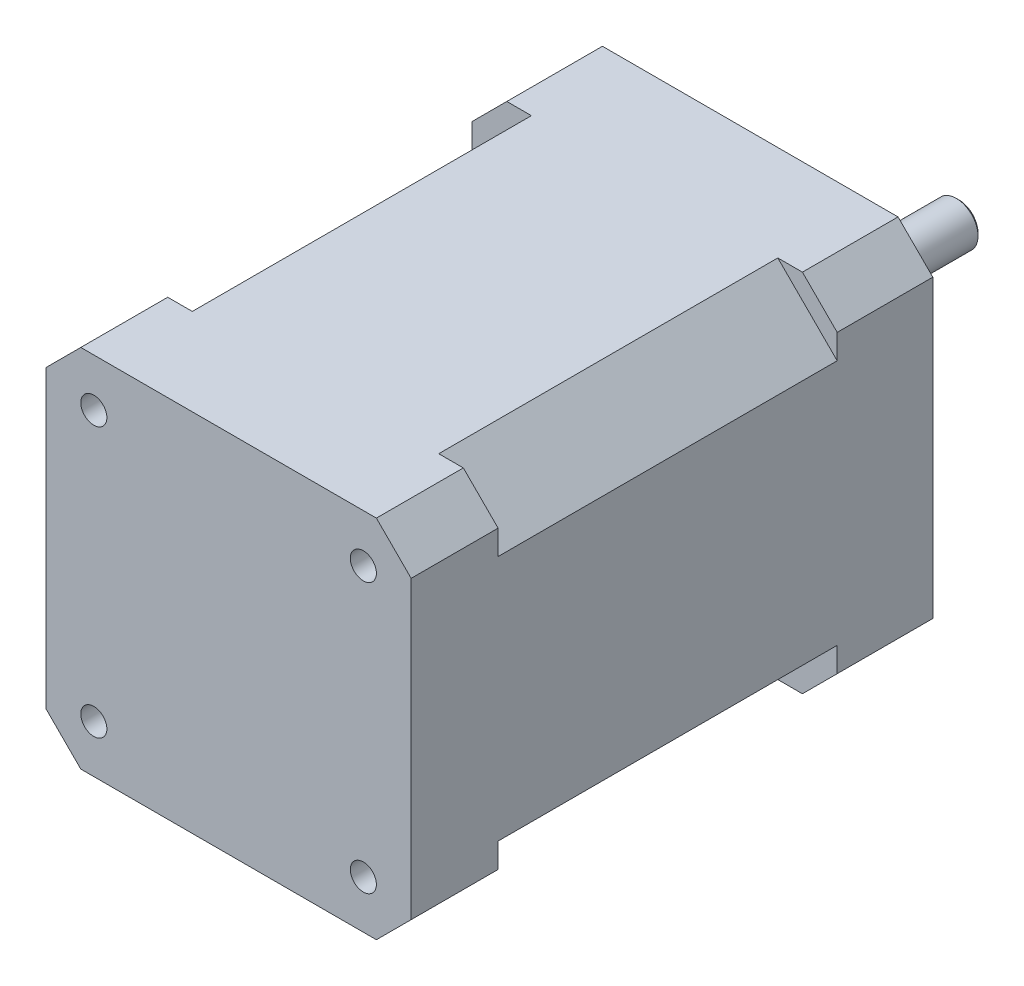
SolidWorks part; units mm, degrees
material "Простая углеродистая сталь"
ref_plane "Спереди" through (0, 0, 0) normal (0, 0, 1) x (1, 0, 0)
ref_plane "Сверху" through (0, 0, 0) normal (0, 1, 0) x (1, 0, 0)
ref_plane "Справа" through (0, 0, 0) normal (1, 0, 0) x (0, 0, -1)
sketch "Эскиз1" plane through (0, 0, 0) normal (0, 0, 1) x (1, 0, 0)
  line L1 (-33.4925, 25.7024) -> (8.5075, 25.7024)
  line L2 (-33.4925, 25.7024) -> (-33.4925, -16.2976)
  line L3 (-33.4925, -16.2976) -> (8.5075, -16.2976)
  line L4 (8.5075, 25.7024) -> (8.5075, -16.2976)
  dimension "D1" = 42
  dimension "D2" = 42
extrude "Бобышка-Вытянуть1" add sketch "Эскиз1" along normal blind 60
sketch "Эскиз2" plane through (0, 0, 0) normal (0, 0, -1) x (-1, 0, 0)
  line L0 (12.4925, 25.7024) -> (12.4925, -16.2976) construction
  line L1 (-8.5075, 25.7024) -> (33.4925, 25.7024) construction
  line L2 (33.4925, -16.2976) -> (-8.5075, -16.2976) construction
  line L3 (12.4925, -16.2976) -> (33.4925, 4.7024) construction
  line L4 (33.4925, 25.7024) -> (33.4925, -16.2976) construction
  line L5 (33.4925, 4.7024) -> (-8.5075, 4.7024) construction
  line L6 (-8.5075, -16.2976) -> (-8.5075, 25.7024) construction
  line L7 (-3.0075, 20.2024) -> (27.9925, 20.2024) construction
  line L8 (27.9925, 20.2024) -> (27.9925, -10.7976) construction
  line L9 (27.9925, -10.7976) -> (-3.0075, -10.7976) construction
  line L10 (-3.0075, -10.7976) -> (-3.0075, 20.2024) construction
  circle A0 centre (-3.0075, 20.2024) radius 1.5
  circle A1 centre (27.9925, 20.2024) radius 1.5
  circle A2 centre (27.9925, -10.7976) radius 1.5
  circle A3 centre (-3.0075, -10.7976) radius 1.5
  dimension "D1" = 3
  dimension "D2" = 3
  dimension "D3" = 3
  dimension "D4" = 3
  dimension "D5" = 31
  dimension "D6" = 31
  dimension "D7" = 31
  dimension "D8" = 15.5
  dimension "D10" = 15.5
  dimension "D9" = 15.5
extrude "Вырез-Вытянуть1" cut sketch "Эскиз2" against normal blind 65
sketch "Эскиз3" plane through (0, 0, 0) normal (0, 0, -1) x (-1, 0, 0)
  line L0 (12.4925, 25.7024) -> (12.4925, -16.2976) construction
  line L1 (-8.5075, 25.7024) -> (33.4925, 25.7024) construction
  line L2 (33.4925, -16.2976) -> (-8.5075, -16.2976) construction
  line L3 (12.4925, -16.2976) -> (33.4925, 4.7024) construction
  line L4 (33.4925, 25.7024) -> (33.4925, -16.2976) construction
  line L5 (33.4925, 4.7024) -> (-8.5075, 4.7024) construction
  line L6 (-8.5075, -16.2976) -> (-8.5075, 25.7024) construction
  circle A0 centre (12.4925, 4.7024) radius 11
  dimension "D1" = 22
extrude "Бобышка-Вытянуть2" add sketch "Эскиз3" along normal blind 2
sketch "Эскиз4" plane through (0, 0, -2) normal (0, 0, -1) x (-1, 0, 0)
  circle A0 centre (12.4925, 4.7024) radius 2.5
  dimension "D1" = 5
extrude "Бобышка-Вытянуть3" add sketch "Эскиз4" along normal blind 22
chamfer "Фаска1" distance 0.3 angle 45 1 edges at (-14.9925, 4.7024, -24)
chamfer "Фаска2" distance 4 angle 45 4 edges at (-33.4925, -16.2976, 30) (8.5075, -16.2976, 30) (-33.4925, 25.7024, 30) (8.5075, 25.7024, 30)
ref_plane "Плоскость1" through (0, 0, 11) normal (0, 0, -1) x (-1, 0, 0)
sketch "Эскиз5" plane through (0, 0, 11) normal (0, 0, -1) x (-1, 0, 0)
  line L0 (-8.5075, 18.874) -> (-1.679, 25.7024)
  line L1 (-8.5075, -12.2976) -> (-8.5075, 21.7024) construction
  line L2 (-4.5075, 25.7024) -> (29.4925, 25.7024) construction
  line L3 (-8.5075, -9.4692) -> (-8.5075, -12.2976)
  line L4 (26.6641, 25.7024) -> (33.4925, 18.874)
  line L5 (33.4925, 21.7024) -> (33.4925, -12.2976) construction
  line L6 (-8.5075, -12.2976) -> (-4.5075, -16.2976)
  line L7 (33.4925, -9.4692) -> (26.6641, -16.2976)
  line L8 (29.4925, -16.2976) -> (-4.5075, -16.2976) construction
  line L9 (-4.5075, -16.2976) -> (-1.679, -16.2976)
  line L10 (-1.679, -16.2976) -> (-8.5075, -9.4692)
  line L11 (26.6641, -16.2976) -> (29.4925, -16.2976)
  line L12 (-4.5075, 25.7024) -> (-8.5075, 21.7024) construction
  line L13 (33.4925, 21.7024) -> (29.4925, 25.7024) construction
  line L14 (29.4925, -16.2976) -> (33.4925, -12.2976) construction
  line L15 (-8.5075, -12.2976) -> (-4.5075, -16.2976) construction
  line L16 (29.4925, -16.2976) -> (33.4925, -12.2976)
  line L17 (33.4925, -12.2976) -> (33.4925, -9.4692)
  line L18 (26.6641, 25.7024) -> (29.4925, 25.7024)
  line L19 (29.4925, 25.7024) -> (33.4925, 21.7024)
  line L20 (33.4925, 21.7024) -> (33.4925, 18.874)
  line L21 (-8.5075, 18.874) -> (-8.5075, 21.7024)
  line L22 (-8.5075, 21.7024) -> (-4.5075, 25.7024)
  line L23 (-4.5075, 25.7024) -> (-1.679, 25.7024)
  dimension "D1" = 2
  dimension "D2" = 2
  dimension "D3" = 2
  dimension "D4" = 2
extrude "Вырез-Вытянуть2" cut sketch "Эскиз5" against normal offset from surface (39 mm away) 10 up to face at (4.5075, -10.7976, 60)
